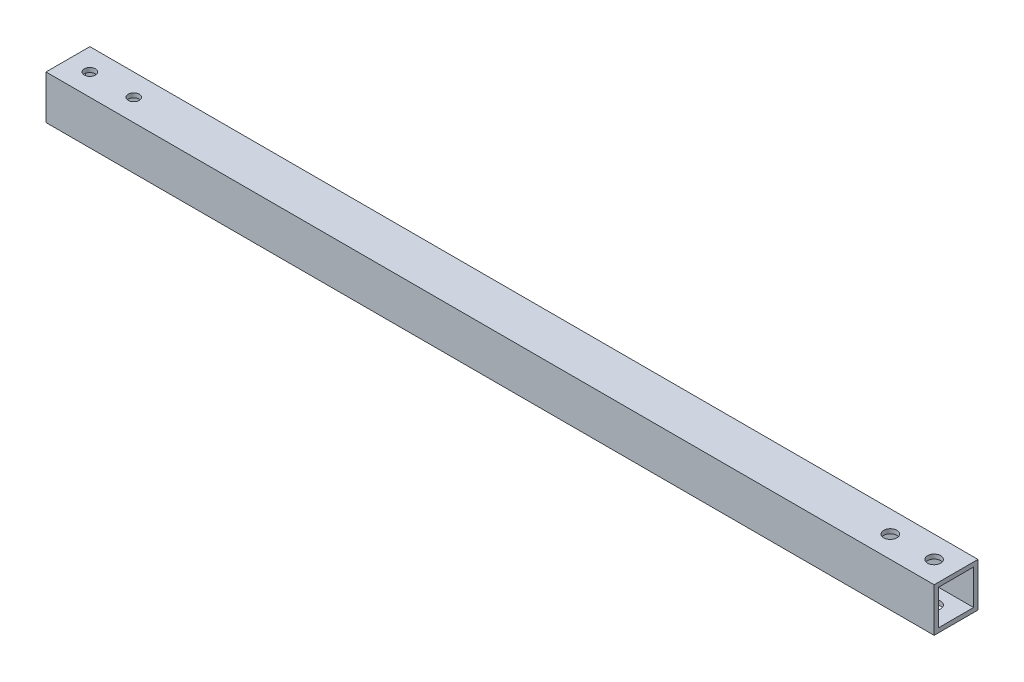
SolidWorks part; units mm, degrees
material "1060 Alloy"
ref_plane "Front Plane" through (0, 0, 0) normal (0, 0, 1) x (1, 0, 0)
ref_plane "Top Plane" through (0, 0, 0) normal (0, 1, 0) x (1, 0, 0)
ref_plane "Right Plane" through (0, 0, 0) normal (1, 0, 0) x (0, 0, -1)
sketch "Sketch1" plane through (0, 0, 0) normal (1, 0, 0) x (0, 0, -1)
  line L0 (8, 8) -> (-8, 8)
  line L1 (-8, 8) -> (-8, -8)
  line L2 (0, 0) -> (0, 27.1676) construction
  line L3 (0, 0) -> (-28.5263, 0) construction
  line L4 (8, 8) -> (8, -8)
  line L5 (8, -8) -> (-8, -8)
  line L7 (-10, 10) -> (10, 10)
  line L8 (-10, 10) -> (-10, -10)
  line L9 (-10, -10) -> (10, -10)
  line L10 (10, 10) -> (10, -10)
  point P8 (0, 8)
  point P11 (8, 0)
  point P12 (-8, 0)
  dimension "D1" = 16
  dimension "D2" = 20
  dimension "D3" = 10
  dimension "D4" = 10
extrude "Boss-Extrude1" add sketch "Sketch1" along normal mid plane 405
sketch "Sketch2" plane through (0, 10, 0) normal (0, 1, 0) x (1, 0, 0)
  line L0 (202.5, 10) -> (202.5, -10) construction
  line L1 (0, 0) -> (225.0132, 0) construction
  circle A0 centre (192.5, 0) radius 3
  circle A1 centre (172.5, 0) radius 3
  dimension "D1" = 6
  dimension "D2" = 6
  dimension "D3" = 20
  dimension "D4" = 10
extrude "Cut-Extrude1" cut sketch "Sketch2" against normal through all
sketch "Sketch3" plane through (0, 10, 0) normal (0, 1, 0) x (1, 0, 0)
  line L0 (0, 0) -> (-238.4052, 0) construction
  line L1 (-202.5, 10) -> (-202.5, -10) construction
  circle A0 centre (-192.5, 0) radius 2.5
  circle A1 centre (-172.5, 0) radius 2.5
  dimension "D1" = 5
  dimension "D2" = 5
  dimension "D3" = 20
  dimension "D4" = 10
extrude "Cut-Extrude2" cut sketch "Sketch3" against normal through all
